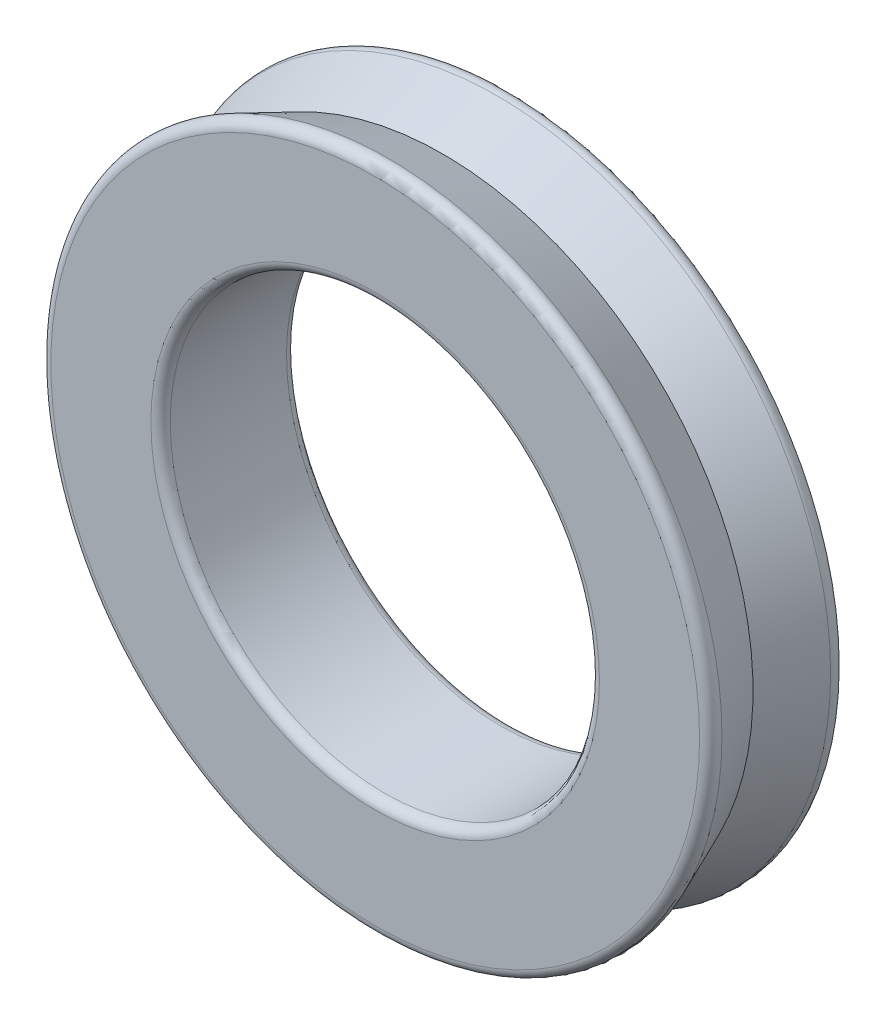
SolidWorks part; units mm, degrees
ref_plane "Front Plane" through (0, 0, 0) normal (0, 0, 1) x (1, 0, 0)
ref_plane "Top Plane" through (0, 0, 0) normal (0, 1, 0) x (1, 0, 0)
ref_plane "Right Plane" through (0, 0, 0) normal (1, 0, 0) x (0, 0, -1)
sketch "Sketch1" plane through (0, 0, 0) normal (0, 0, 1) x (1, 0, 0)
  circle A0 centre (0, 0) radius 11.075
  circle A1 centre (0, 0) radius 17.5
  dimension "D1" = 22.15
  dimension "D2" = 35
extrude "Boss-Extrude1" add sketch "Sketch1" along normal blind 7
sketch "Sketch2" plane through (0, 0, 0) normal (0, 1, 0) x (1, 0, 0)
  line L0 (17.5, 0) -> (16, -3.5)
  line L1 (16, -3.5) -> (17.5, -7)
  line L2 (17.5, 0) -> (17.5, -7)
  line L3 (0, 0) -> (0, -5.4003) construction
  dimension "D1" = 16
revolve "Cut-Revolve1" cut sketch "Sketch2" angle 360 about L3
fillet "Fillet1" radius 0.5 2 edges at (-17.5, 0, 7) (-17.5, 0, 0)
fillet "Fillet2" radius 0.5 2 edges at (11.075, 0, 7) (11.075, 0, 0)
